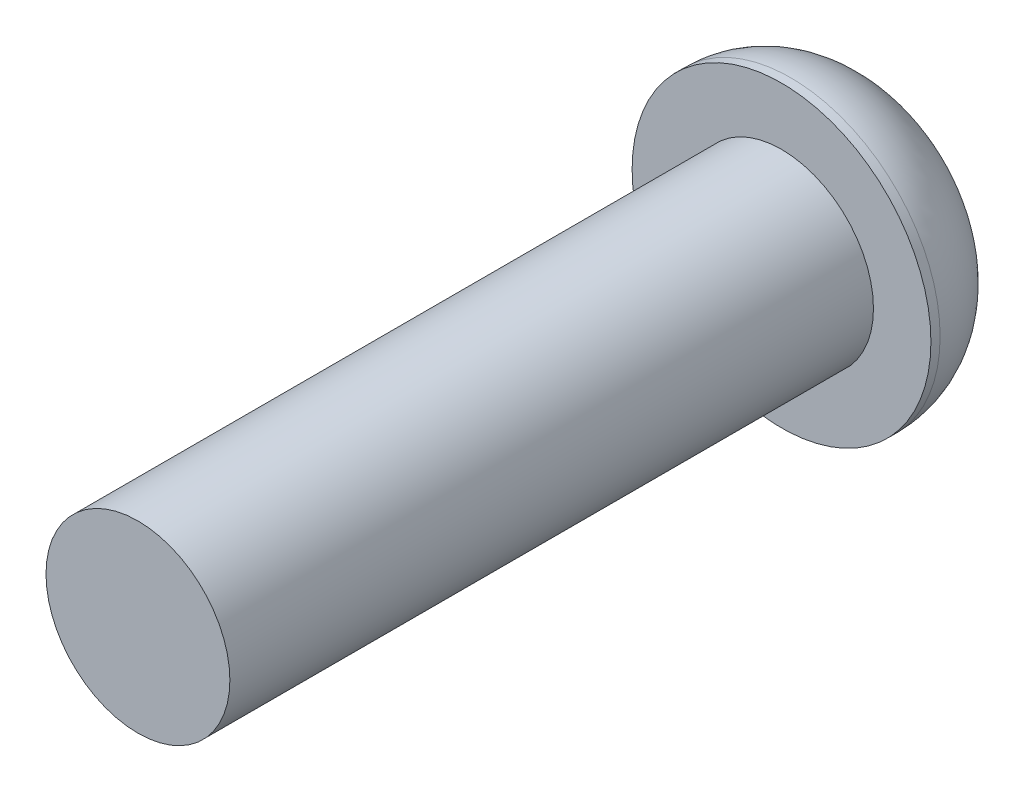
SolidWorks part; units mm, degrees
ref_plane "前视基准面" through (0, 0, 0) normal (0, 0, 1) x (1, 0, 0)
ref_plane "上视基准面" through (0, 0, 0) normal (0, 1, 0) x (1, 0, 0)
ref_plane "右视基准面" through (0, 0, 0) normal (1, 0, 0) x (0, 0, -1)
sketch "草图1" plane through (0, 0, 0) normal (0, 0, 1) x (1, 0, 0)
  circle A0 centre (0, 0) radius 2
  dimension "D1" = 4
extrude "凸台-拉伸1" add sketch "草图1" along normal blind 14
sketch "草图2" plane through (0, 0, 0) normal (0, 0, -1) x (-1, 0, 0)
  circle A0 centre (0, 0) radius 3.25
  dimension "D1" = 6.5
extrude "凸台-拉伸2" add sketch "草图2" along normal blind 2.2
fillet "圆角1" radius 2 1 edges at (-3.25, 0, -2.2)
sketch "草图3" plane through (0, 0, -2.2) normal (0, 0, -1) x (-1, 0, 0)
  line L0 (0, 3.24) -> (0, -3.24) construction
  line L1 (-3.24, 0) -> (3.24, 0) construction
  line L2 (-3.24, 0.25) -> (3.24, 0.25) construction
  line L3 (0.25, 3.24) -> (0.25, -3.24) construction
  line L4 (-3.24, -0.25) -> (3.24, -0.25) construction
  line L5 (-0.25, 3.24) -> (-0.25, -3.24) construction
  line L7 (3.24, 0.25) -> (3.24, -0.25)
  line L8 (-0.25, 3.24) -> (0.25, 3.24)
  line L10 (-0.25, 3.24) -> (-0.25, 0.25)
  line L11 (0.25, 3.24) -> (0.25, 0.25)
  line L12 (3.24, 0.25) -> (0.25, 0.25)
  line L13 (3.24, -0.25) -> (0.25, -0.25)
  line L15 (0.25, -3.24) -> (0.25, -0.25)
  line L16 (-0.25, -3.24) -> (-0.25, -0.25)
  line L17 (0.25, -3.24) -> (-0.25, -3.24)
  line L18 (-3.24, -0.25) -> (-0.25, -0.25)
  line L19 (-3.24, 0.25) -> (-0.25, 0.25)
  line L20 (-3.24, -0.25) -> (-3.24, 0.25)
  line L21 (3.24, 0.25) -> (3.24, -0.25) [skipped]
  circle A1 centre (0, 0) radius 3.24 construction
  dimension "D1" = 0.25
  dimension "D2" = 0.25
  dimension "D3" = 4
extrude "切除-拉伸1" cut sketch "草图3" against normal blind 0.5
